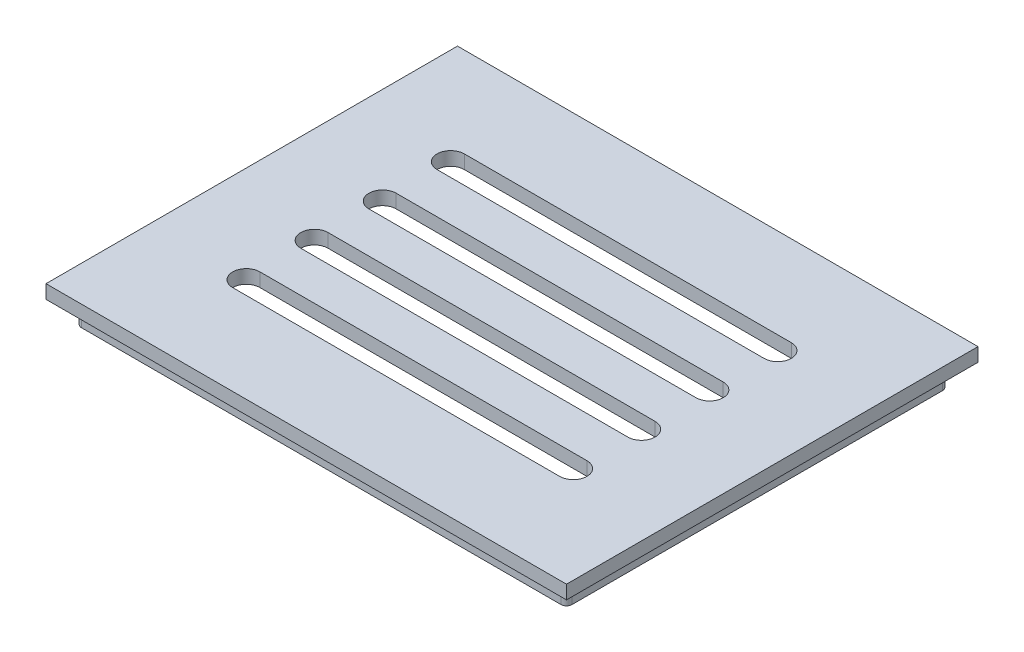
SolidWorks part; units mm, degrees
ref_plane "Front Plane" through (0, 0, 0) normal (0, 0, 1) x (1, 0, 0)
ref_plane "Top Plane" through (0, 0, 0) normal (0, 1, 0) x (1, 0, 0)
ref_plane "Right Plane" through (0, 0, 0) normal (1, 0, 0) x (0, 0, -1)
sketch "Sketch1" plane through (0, 0, 0) normal (0, 1, 0) x (1, 0, 0)
  line L1 (-45, 35) -> (45, 35)
  line L2 (-45, 35) -> (-45, -35)
  line L3 (-45, -35) -> (45, -35)
  line L4 (45, 35) -> (45, -35)
  line L5 (-45, 35) -> (45, -35) construction
  line L6 (-45, -35) -> (45, 35) construction
  point P0 (0, 0)
  dimension "D1" = 90
  dimension "D2" = 70
extrude "Extrude-Thin1" add sketch "Sketch1" along normal blind 4 thin
sketch "Sketch2" plane through (0, 4, 0) normal (0, 1, 0) x (1, 0, 0)
  line L0 (-47.75, 37.75) -> (-47.75, -37.75)
  line L1 (-47.75, -37.75) -> (47.75, -37.75)
  line L2 (47.75, -37.75) -> (47.75, 37.75)
  line L3 (47.75, 37.75) -> (-47.75, 37.75)
  line L4 (45, -35) -> (45, 35)
  line L5 (45, 35) -> (-45, 35)
  line L6 (-45, 35) -> (-45, -35)
  line L7 (-45, -35) -> (45, -35)
  line L8 (45, -35) -> (45, 35)
  line L9 (45, 35) -> (-45, 35)
  line L10 (-45, 35) -> (-45, -35)
  line L11 (-45, -35) -> (45, -35)
  line L12 (-30, -18.75) -> (30, -18.75) construction
  line L13 (-30, -16.25) -> (30, -16.25)
  line L14 (-30, -21.25) -> (30, -21.25)
  line L15 (-30, -6.25) -> (30, -6.25) construction
  line L18 (-30, -3.75) -> (30, -3.75)
  line L21 (45, -35) -> (45, 35) construction
  line L22 (45, 35) -> (-45, 35) construction
  line L23 (-30, -8.75) -> (30, -8.75)
  line L26 (-30, 6.25) -> (30, 6.25) construction
  line L27 (-30, 8.75) -> (30, 8.75)
  line L28 (-30, 3.75) -> (30, 3.75)
  line L29 (-30, 18.75) -> (30, 18.75) construction
  line L30 (-30, 21.25) -> (30, 21.25)
  line L31 (-30, 16.25) -> (30, 16.25)
  arc A0 (-30, -16.25) -> (-30, -21.25) centre (-30, -18.75) ccw
  arc A1 (30, -21.25) -> (30, -16.25) centre (30, -18.75) ccw
  arc A8 (-30, -3.75) -> (-30, -8.75) centre (-30, -6.25) ccw
  arc A9 (30, -8.75) -> (30, -3.75) centre (30, -6.25) ccw
  arc A10 (-30, 8.75) -> (-30, 3.75) centre (-30, 6.25) ccw
  arc A11 (30, 3.75) -> (30, 8.75) centre (30, 6.25) ccw
  arc A12 (-30, 21.25) -> (-30, 16.25) centre (-30, 18.75) ccw
  arc A13 (30, 16.25) -> (30, 21.25) centre (30, 18.75) ccw
  point P10 (0, -18.75)
  point P21 (0, -6.25)
  point P28 (0, 6.25)
  point P37 (0, 18.75)
  dimension "D6" = 4
  dimension "D3" = 60
  dimension "D4" = 13.75
  dimension "D5" = 5
  dimension "D7" = 7.5
  dimension "D2" = 95.5
  dimension "D1" = 0
extrude "Boss-Extrude1" add sketch "Sketch2" along normal blind 2.5
fillet "Fillet1" radius 1 4 edges at (-45, 2, -35) (45, 2, -35) (-45, 2, 35) (45, 2, 35)
fillet "Fillet2" radius 0.75 8 edges at (-44.7071, 4, 34.7071) (-45, 4, 0) (-44.7071, 4, -34.7071) (0, 4, -35) (44.7071, 4, -34.7071) (45, 4, 0) (44.7071, 4, 34.7071) (0, 4, 35)
